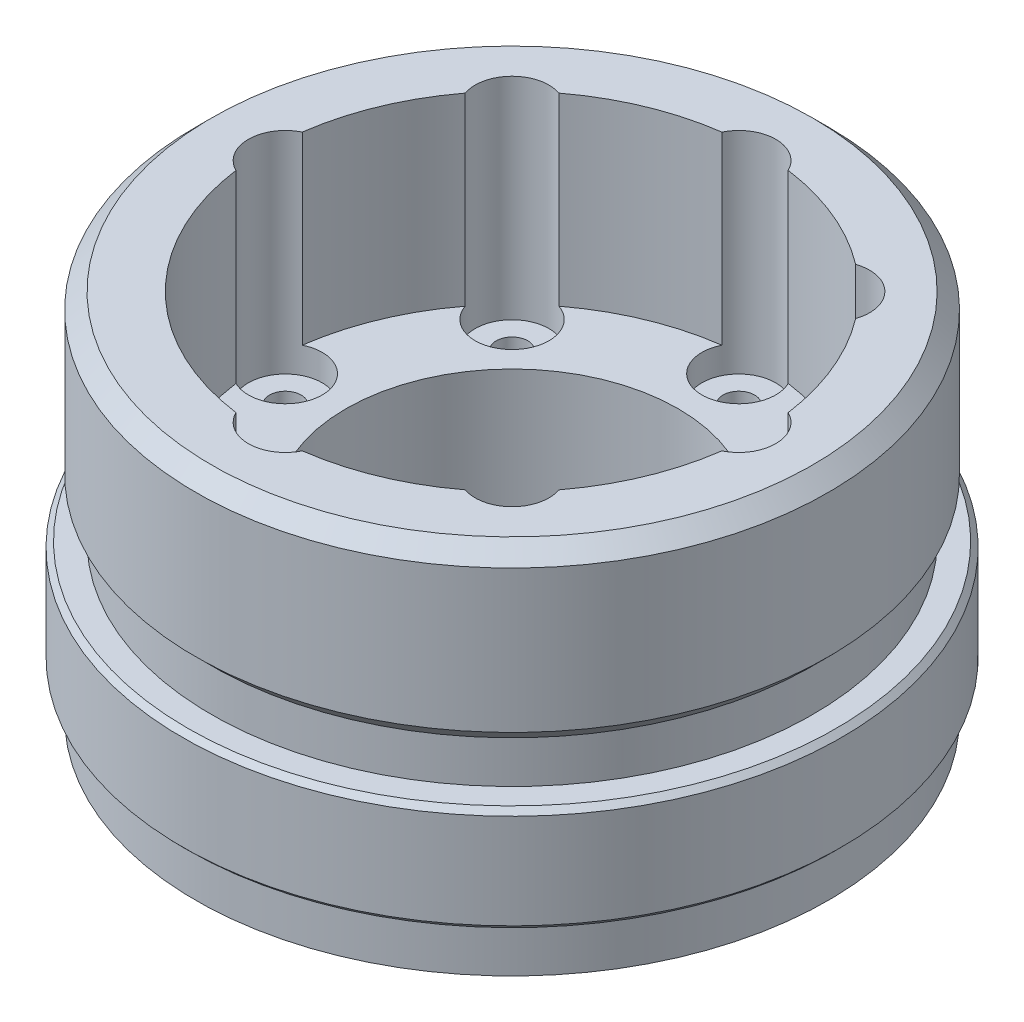
SolidWorks part; units mm, degrees
material "Алюминиевая бронза"
ref_plane "Спереди" through (0, 0, 0) normal (0, 0, 1) x (1, 0, 0)
ref_plane "Сверху" through (0, 0, 0) normal (0, 1, 0) x (1, 0, 0)
ref_plane "Справа" through (0, 0, 0) normal (1, 0, 0) x (0, 0, -1)
other "Табл. исп."
sketch "Эскиз1" plane through (0, 0, 0) normal (0, 0, 1) x (1, 0, 0)
  line L0 (0, 0) -> (0, 68.0615) construction
  line L1 (-42, 0) -> (-60, 0)
  line L2 (-60, 0) -> (-60, 9)
  line L3 (-60, 9) -> (-61.5, 9)
  line L4 (-62.5, 10) -> (-62.5, 28)
  line L5 (-62.5, 28) -> (-61.5, 29)
  line L6 (-61.5, 29) -> (-57, 29)
  line L7 (-57, 29) -> (-57, 37)
  line L8 (-57, 37) -> (-60, 40)
  line L9 (-60, 40) -> (-60, 67)
  line L10 (-60, 67) -> (-57, 70)
  line L11 (-57, 70) -> (-46.5, 70)
  line L12 (-46.5, 70) -> (-46.5, 35)
  line L13 (-46.5, 35) -> (-31.5, 35)
  line L14 (-31.5, 35) -> (-31.5, 10)
  line L15 (-31.5, 10) -> (-42, 10)
  line L16 (-42, 10) -> (-42, 0)
  line L17 (-61.5, 9) -> (-62.5, 10)
  dimension "D1" = 84
  dimension "D2" = 120
  dimension "D3" = 9
  dimension "D4" = 125
  dimension "D5" = 45
  dimension "D6" = 1
  dimension "D7" = 10
  dimension "D8" = 63
  dimension "D9" = 25
  dimension "D10" = 120
  dimension "D11" = 114
  dimension "D12" = 45
  dimension "D13" = 3
  dimension "D14" = 93
  dimension "D15" = 8
  dimension "D16" = 70
  dimension "D17" = 29
revolve "Повернуть1" add sketch "Эскиз1" angle 360 about L0
sketch "Эскиз5" plane through (0, 0, 0) normal (0, 0, 1) x (1, 0, 0)
  line L0 (-43, 84.5121) -> (-43, -16.1088) construction
  line L1 (-43, 0) -> (-46, 0)
  line L2 (-46, 0) -> (-46, 30)
  line L3 (-46, 30) -> (-50, 30)
  line L4 (-50, 30) -> (-50, 70)
  line L5 (-50, 70) -> (-43, 70)
  line L6 (-43, 70) -> (-43, 0)
  line L7 (31.5, 35) -> (-31.5, 35) construction
  line L8 (46.5, 70) -> (-46.5, 70) construction
  line L9 (-42, 0) -> (42, 0) construction
  dimension "D1" = 43
  dimension "D2" = 6
  dimension "D3" = 5
  dimension "D4" = 14
revolve "Вырез-Повернуть1" cut sketch "Эскиз5" angle 360 about L0
pattern_circular "Круговой массив1" count 8 over 360 about axis through (0, 0, 0) along (0, 1, 0) skipping 7 of "Вырез-Повернуть1"
